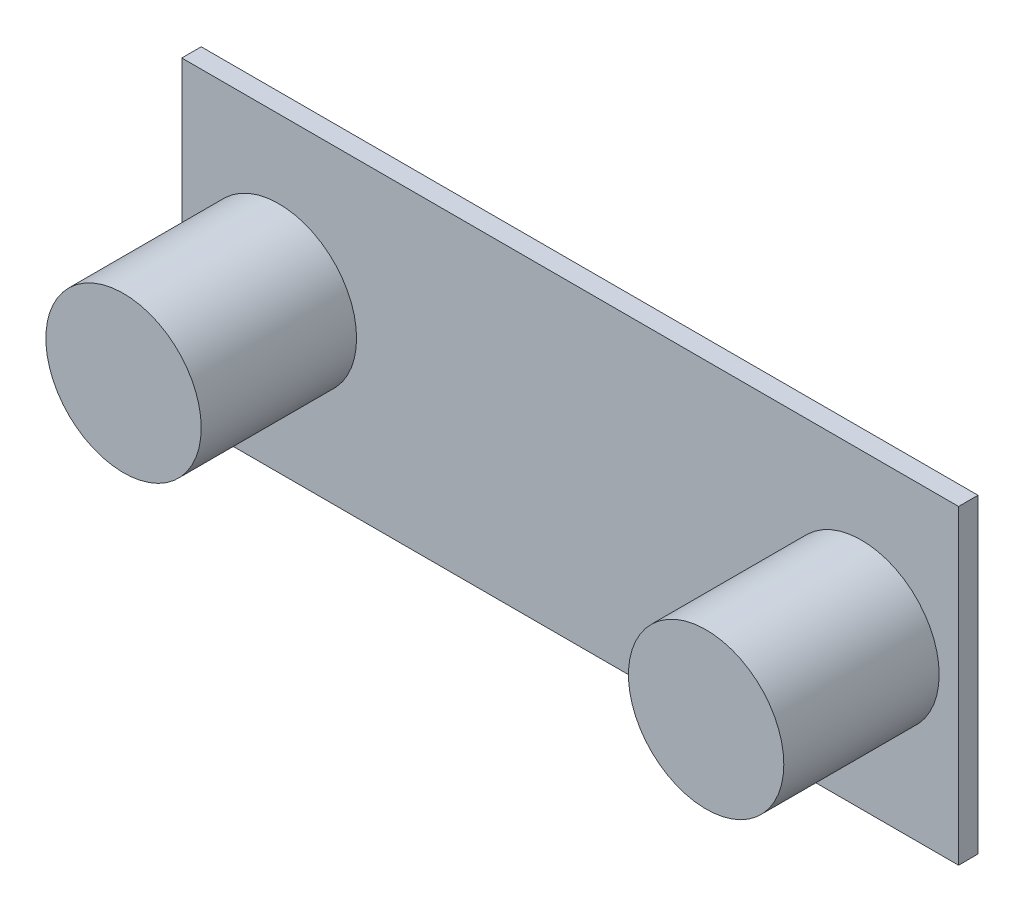
SolidWorks part; units mm, degrees
ref_plane "Front Plane" through (0, 0, 0) normal (0, 0, 1) x (1, 0, 0)
ref_plane "Top Plane" through (0, 0, 0) normal (0, 1, 0) x (1, 0, 0)
ref_plane "Right Plane" through (0, 0, 0) normal (1, 0, 0) x (0, 0, -1)
sketch "Sketch1" plane through (0, 0, 0) normal (0, 0, 1) x (1, 0, 0)
  line L1 (-40, 16) -> (40, 16)
  line L2 (-40, 16) -> (-40, -16)
  line L3 (-40, -16) -> (40, -16)
  line L4 (40, 16) -> (40, -16)
  point P4 (0, 0)
  dimension "D1" = 80
  dimension "D2" = 32
  dimension "D3" = 40
  dimension "D4" = 16
extrude "Boss-Extrude1" add sketch "Sketch1" along normal blind 2
sketch "Sketch3" plane through (0, 0, 2) normal (0, 0, 1) x (1, 0, 0)
  line L0 (-40, 16) -> (-40, -16) construction
  circle A0 centre (-30, 0) radius 8
  circle A1 centre (30, 0) radius 8
  point P4 (-38, 0)
  dimension "D3" = 16
  dimension "D4" = 16
  dimension "D1" = 60
  dimension "D2" = 2
extrude "Boss-Extrude2" add sketch "Sketch3" along normal blind 16
